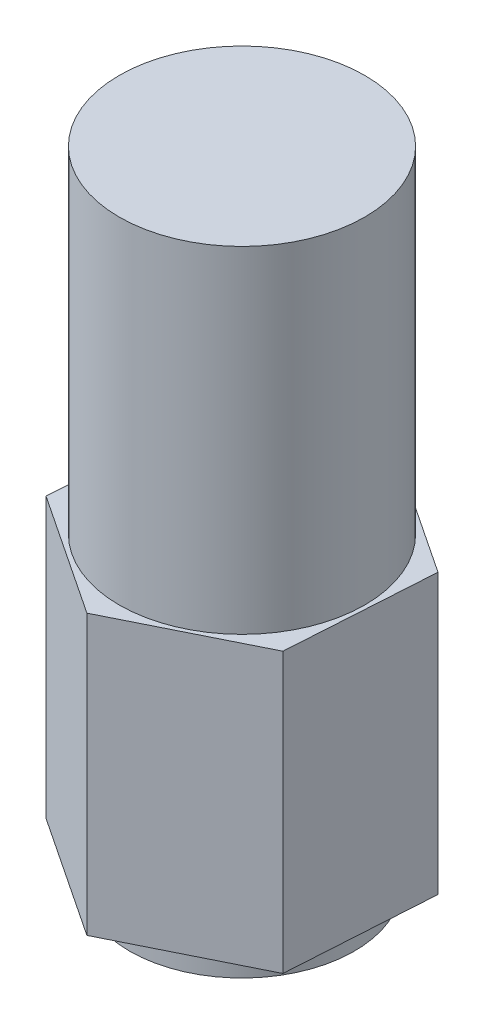
SolidWorks part; units mm, degrees
ref_plane "前视基准面" through (0, 0, 0) normal (0, 0, 1) x (1, 0, 0)
ref_plane "上视基准面" through (0, 0, 0) normal (0, 1, 0) x (1, 0, 0)
ref_plane "右视基准面" through (0, 0, 0) normal (1, 0, 0) x (0, 0, -1)
other "Configuration Table"
sketch "草图1" plane through (0, 0, 0) normal (0, 1, 0) x (1, 0, 0)
  circle A0 centre (0, 0) radius 4.35
  dimension "D1" = 8.7
extrude "凸台-拉伸1" add sketch "草图1" along normal blind 1
sketch "草图2" plane through (0, 1, 0) normal (0, 1, 0) x (1, 0, 0)
  line L1 (4.7129, -3.1307) -> (5.0678, 2.5162)
  line L2 (5.0678, 2.5162) -> (0.3548, 5.6469)
  line L3 (0.3548, 5.6469) -> (-4.7129, 3.1307)
  line L4 (-4.7129, 3.1307) -> (-5.0678, -2.5162)
  line L5 (-5.0678, -2.5162) -> (-0.3548, -5.6469)
  line L6 (-0.3548, -5.6469) -> (4.7129, -3.1307)
  circle A0 centre (0, 0) radius 4.9 construction
  dimension "D1" = 9.8
extrude "凸台-拉伸2" add sketch "草图2" along normal blind 10.8
sketch "草图3" plane through (0, 11.8, 0) normal (0, 1, 0) x (1, 0, 0)
  circle A0 centre (0, 0) radius 4.75
  dimension "D1" = 9.5
extrude "凸台-拉伸3" add sketch "草图3" along normal blind 13
